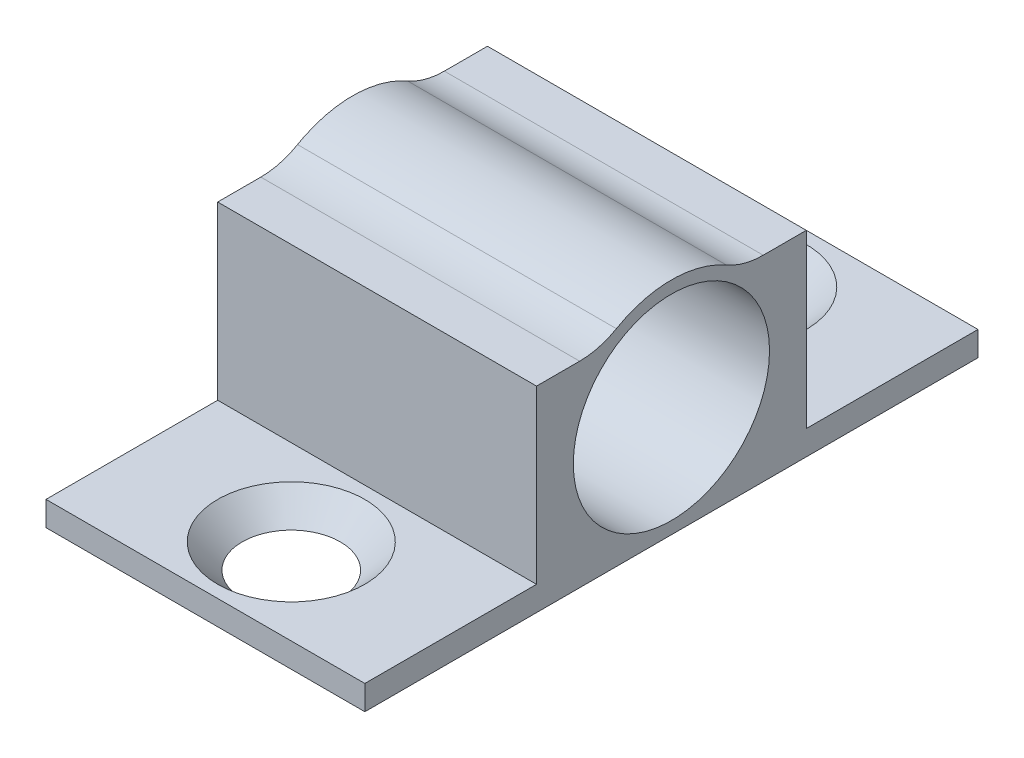
SolidWorks part; units mm, degrees
ref_plane "Front Plane" through (0, 0, 0) normal (0, 0, 1) x (1, 0, 0)
ref_plane "Top Plane" through (0, 0, 0) normal (0, 1, 0) x (1, 0, 0)
ref_plane "Right Plane" through (0, 0, 0) normal (1, 0, 0) x (0, 0, -1)
sketch "Sketch1" plane through (0, 0, 0) normal (0, 1, 0) x (1, 0, 0)
  line L1 (0, 0) -> (13, 0)
  line L2 (0, 0) -> (0, 25)
  line L3 (0, 25) -> (13, 25)
  line L4 (13, 0) -> (13, 25)
  dimension "D1" = 25
  dimension "D2" = 13
extrude "Boss-Extrude1" add sketch "Sketch1" along normal blind 1
sketch "Sketch3" plane through (0, 1, 0) normal (0, 1, 0) x (1, 0, 0)
  line L0 (0, 25) -> (0, 0) construction
  line L1 (0, 18) -> (13, 18)
  line L2 (0, 18) -> (0, 7)
  line L3 (0, 7) -> (13, 7)
  line L4 (13, 18) -> (13, 7)
  line L5 (13, 0) -> (13, 25) construction
  line L6 (13, 25) -> (0, 25) construction
  line L7 (0, 0) -> (13, 0) construction
  point P8 (6.5, 25)
  dimension "D1" = 7
  dimension "D2" = 7
extrude "Boss-Extrude2" add sketch "Sketch3" along normal blind 7
sketch "Sketch4" plane through (13, 0, 0) normal (1, 0, 0) x (0, 0, -1)
  line L0 (7, 4.5) -> (18, 4.5) construction
  line L1 (7, 8) -> (7, 1) construction
  line L2 (18, 8) -> (18, 1) construction
  line L3 (12.5, 8) -> (12.5, 0) construction
  line L4 (7, 8) -> (18, 8) construction
  line L5 (0, 0) -> (25, 0) construction
  circle A0 centre (12.5, 4.5) radius 4.5
  dimension "D1" = 9
extrude "Boss-Extrude3" add sketch "Sketch4" against normal through all
sketch "Sketch6" plane through (0, 0, 0) normal (-1, 0, 0) x (0, 0, 1)
  circle A0 centre (-12.5, 4.5) radius 4
  dimension "D1" = 8
extrude "Cut-Extrude1" cut sketch "Sketch6" against normal through all
fillet "Fillet1" radius 3 2 edges at (6.5, 8, -9.6716) (6.5, 8, -15.3284)
sketch "Sketch14" plane through (0, 1, 0) normal (0, 1, 0) x (1, 0, 0)
  line L0 (0, 3.5) -> (13, 3.5) construction
  line L1 (0, 7) -> (0, 0) construction
  line L2 (13, 0) -> (13, 7) construction
  line L3 (6.5, 0) -> (6.5, 7) construction
  line L4 (0, 0) -> (13, 0) construction
  line L5 (0, 7) -> (13, 7) construction
hole_wizard "CSK for M3 Oval Head Machine Screw2" positions "Sketch16" profile "Sketch15" countersink size "M3" standard "ANSI Metric" end condition through all
sketch "Sketch16" plane through (0, 1, 0) normal (0, 1, 0) x (1, 0, 0)
  line L0 (0, 3.5) -> (13, 3.5) construction
  point P0 (6.5, 3.5)
  point P4 (6.5, 21.5)
sketch "Sketch15" plane through (6.5, 1, -3.5) normal (1, 0, 0) x (0, 0, 1)
  line L0 (0, 0) -> (0, 1)
  line L1 (0, 1) -> (1.75, 1)
  line L2 (1.75, 1) -> (1.75, 1.25)
  line L3 (1.75, 1.25) -> (3, 0)
  line L5 (3, 0) -> (0, 0)
  line L6 (-1.75, 1.25) -> (-3, 0) construction
  line L11 (0, -6.35) -> (0, 107.95) construction
  dimension "Thru Hole Dia." = 3.5
  dimension "Thru Hole Depth" = 1
  dimension "Near C'Sink Dia." = 6
  dimension "Near C'Sink Angle" = 90
